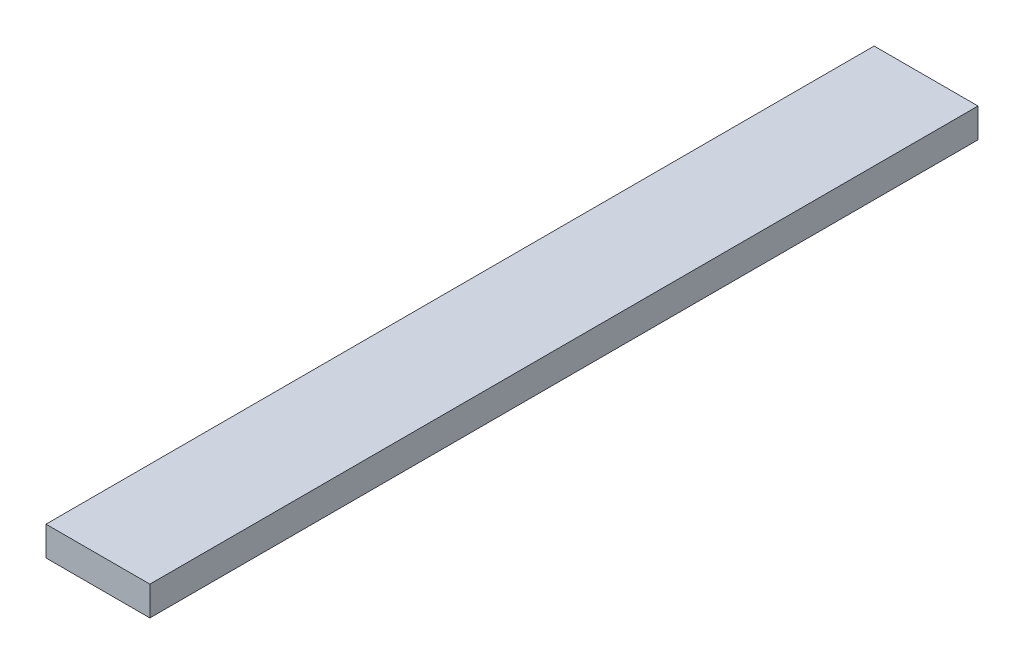
SolidWorks part; units mm, degrees
ref_plane "Front Plane" through (0, 0, 0) normal (0, 0, 1) x (1, 0, 0)
ref_plane "Top Plane" through (0, 0, 0) normal (0, 1, 0) x (1, 0, 0)
ref_plane "Right Plane" through (0, 0, 0) normal (1, 0, 0) x (0, 0, -1)
sketch "Sketch1" plane through (0, 0, 0) normal (0, 0, 1) x (1, 0, 0)
  line L1 (0, 0) -> (45, 0)
  line L2 (0, 0) -> (0, 12.7)
  line L3 (0, 12.7) -> (45, 12.7)
  line L4 (45, 0) -> (45, 12.7)
  dimension "D1" = 45
  dimension "D2" = 12.7
extrude "Boss-Extrude1" add sketch "Sketch1" along normal blind 358.775
